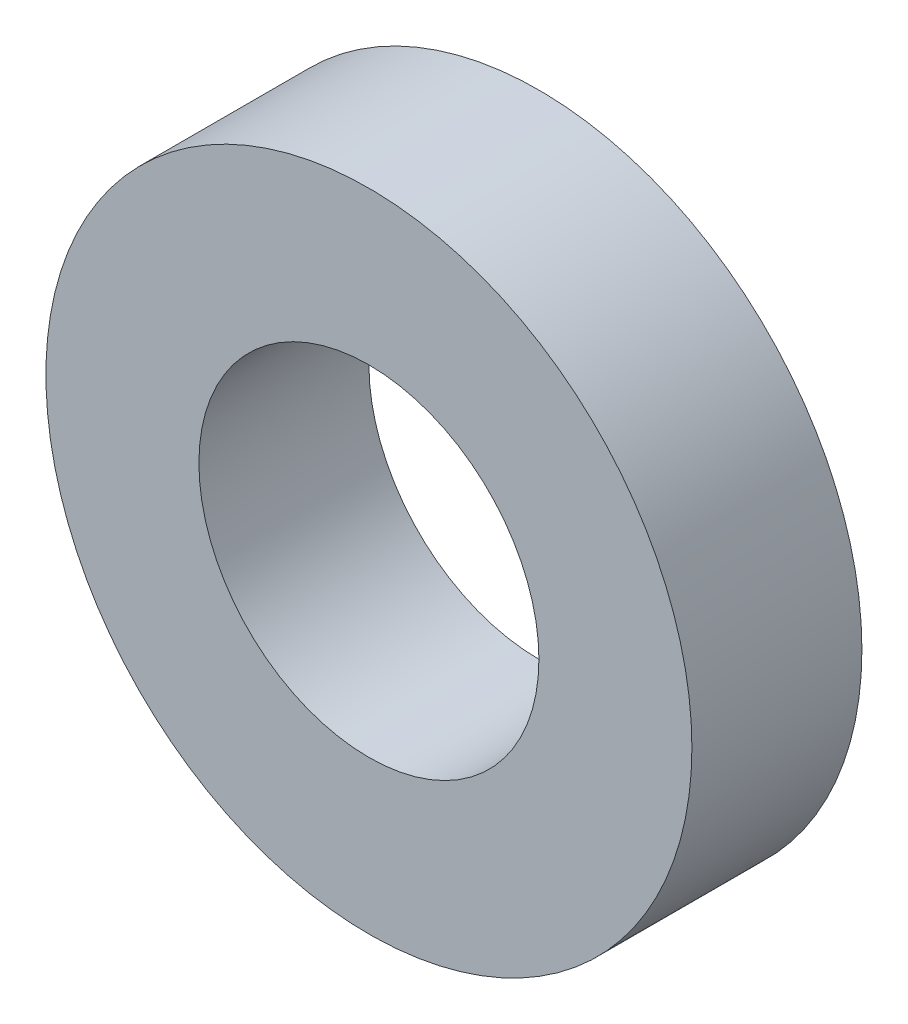
SolidWorks part; units mm, degrees
material "SKD11淬火HRC56-60"
ref_plane "前基準面" through (0, 0, 0) normal (0, 0, 1) x (1, 0, 0)
ref_plane "上基準面" through (0, 0, 0) normal (0, 1, 0) x (1, 0, 0)
ref_plane "右基準面" through (0, 0, 0) normal (1, 0, 0) x (0, 0, -1)
sketch "草图1" plane through (0, 0, 0) normal (0, 0, 1) x (1, 0, 0)
  circle A0 centre (0, 0) radius 9.5
  circle A1 centre (0, 0) radius 5
  dimension "D1" = 19
  dimension "D2" = 10
extrude "凸台-拉伸1" add sketch "草图1" along normal blind 5
